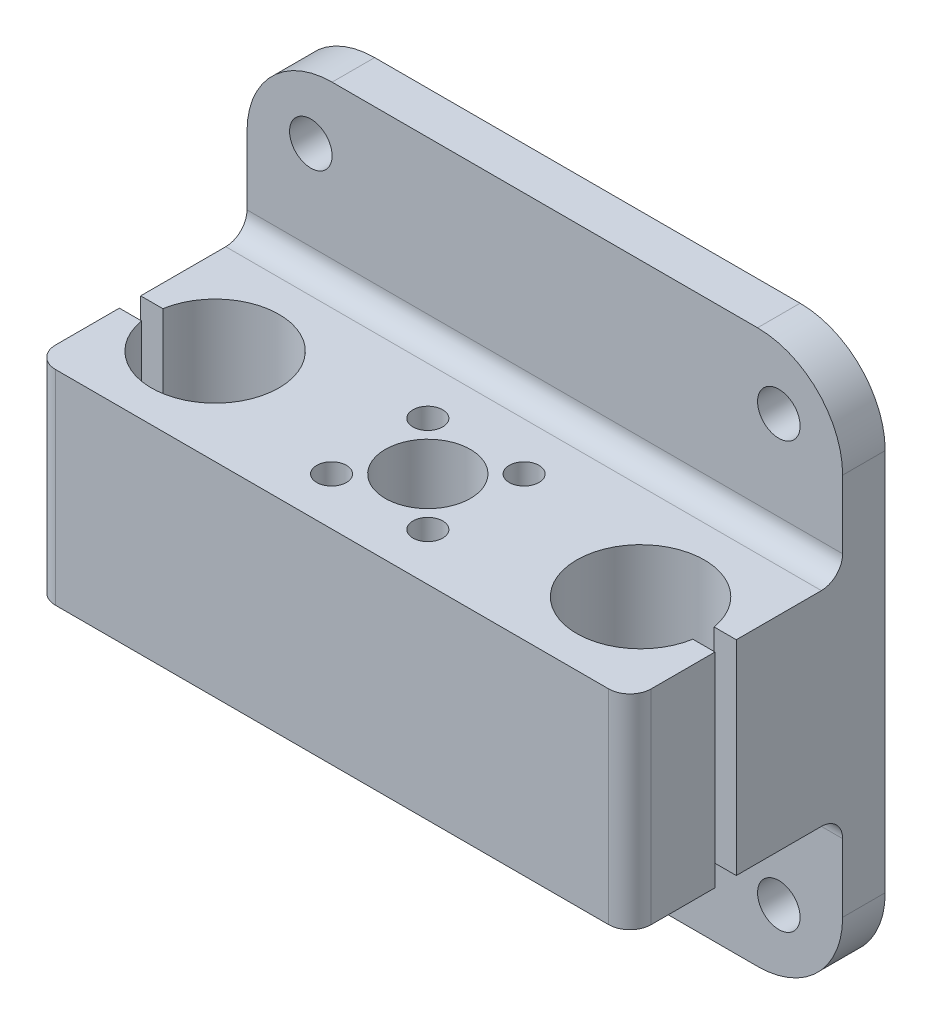
SolidWorks part; units mm, degrees
ref_plane "Front Plane" through (0, 0, 0) normal (0, 0, 1) x (1, 0, 0)
ref_plane "Top Plane" through (0, 0, 0) normal (0, 1, 0) x (1, 0, 0)
ref_plane "Right Plane" through (0, 0, 0) normal (1, 0, 0) x (0, 0, -1)
sketch "Sketch1" plane through (0, 0, 0) normal (0, 0, 1) x (1, 0, 0)
  line L0 (-50.4878, 10.6707) -> (19.5122, 10.6707) construction
  line L1 (-50.4878, 18.1707) -> (19.5122, 18.1707)
  line L2 (-50.4878, 18.1707) -> (-50.4878, -46.8293)
  line L3 (-50.4878, -46.8293) -> (19.5122, -46.8293)
  line L4 (19.5122, 18.1707) -> (19.5122, -46.8293)
  line L5 (19.5122, -39.3293) -> (-50.4878, -39.3293) construction
  circle A0 centre (-42.9878, 10.6707) radius 2.5
  circle A1 centre (12.0122, 10.6707) radius 2.5
  circle A2 centre (-42.9878, -39.3293) radius 2.5
  circle A3 centre (12.0122, -39.3293) radius 2.5
  dimension "D5" = 7.5
  dimension "D6" = 7.5
  dimension "D7" = 7.5
  dimension "D1" = 70
  dimension "D2" = 65
  dimension "D3" = 7.5
  dimension "D4" = 7.5
  dimension "D8" = 7.5
extrude "Boss-Extrude1" add sketch "Sketch1" along normal blind 5
fillet "Fillet1" radius 10 4 edges at (19.5122, -46.8293, 2.5) (19.5122, 18.1707, 2.5) (-50.4878, -46.8293, 2.5) (-50.4878, 18.1707, 2.5)
sketch "Sketch2" plane through (0, 0, 5) normal (0, 0, 1) x (1, 0, 0)
  line L0 (-50.4878, -14.3293) -> (19.5122, -14.3293) construction
  line L1 (-50.4878, 8.1707) -> (-50.4878, -36.8293) construction
  line L2 (19.5122, -36.8293) -> (19.5122, 8.1707) construction
  line L3 (-15.4878, 18.1707) -> (-15.4878, -46.8293) construction
  line L4 (9.5122, 18.1707) -> (-40.4878, 18.1707) construction
  line L5 (-40.4878, -46.8293) -> (9.5122, -46.8293) construction
  line L7 (19.5122, -26.3293) -> (-50.4878, -26.3293)
  line L8 (19.5122, -26.3293) -> (19.5122, -2.3293)
  line L9 (19.5122, -2.3293) -> (-50.4878, -2.3293)
  line L10 (-50.4878, -26.3293) -> (-50.4878, -2.3293)
  line L11 (19.5122, -26.3293) -> (-50.4878, -2.3293) construction
  line L12 (19.5122, -2.3293) -> (-50.4878, -26.3293) construction
  point P12 (-15.4878, -14.3293)
  dimension "D1" = 70
  dimension "D2" = 24
extrude "Boss-Extrude2" add sketch "Sketch2" along normal blind 25
fillet "Fillet2" radius 2.5 2 edges at (-15.4878, -26.3293, 5) (-15.4878, -2.3293, 5)
sketch "Sketch3" plane through (0, -2.3293, 0) normal (0, 1, 0) x (1, 0, 0)
  line L0 (-50.4878, -18.75) -> (19.5122, -18.75) construction
  line L1 (-50.4878, -30) -> (-50.4878, -7.5) construction
  line L2 (19.5122, -30) -> (19.5122, -7.5) construction
  circle A0 centre (-15.4878, -18.75) radius 5
  circle A1 centre (-40.4878, -18.75) radius 7.5
  circle A2 centre (9.5122, -18.75) radius 7.5
  dimension "D1" = 25
  dimension "D3" = 10
  dimension "D4" = 15
  dimension "D5" = 15
  dimension "D2" = 25
extrude "Cut-Extrude1" cut sketch "Sketch3" against normal blind 30
sketch "Sketch4" plane through (0, -2.3293, 0) normal (0, 1, 0) x (1, 0, 0)
  line L0 (-15.4878, -18.75) -> (-26.7542, -7.4836) construction
  line L1 (-26.7542, -7.4836) -> (-2.6885, -31.5494) construction
  line L2 (-2.6885, -31.5494) -> (-15.4878, -18.75) construction
  line L3 (-15.4878, -18.75) -> (-3.9042, -7.1664) construction
  line L4 (-3.9042, -7.1664) -> (-29.7686, -33.0308) construction
  line L6 (-15.4878, -18.75) -> (-26.0601, -10.2476) construction
  line L7 (-38.5195, -27.2656) -> (6.5388, -27.2656) construction
  circle A0 centre (-21.1447, -13.0931) radius 1.75
  circle A1 centre (-9.831, -13.0931) radius 1.75
  circle A2 centre (-9.831, -24.4069) radius 1.75
  circle A3 centre (-21.1447, -24.4069) radius 1.75
  dimension "D1" = 8
  dimension "D2" = 8
  dimension "D3" = 8
  dimension "D4" = 8
  dimension "D5" = 135
extrude "Cut-Extrude2" cut sketch "Sketch4" against normal blind 30
fillet "Fillet3" radius 2.5 2 edges at (19.5122, -14.3293, 30) (-50.4878, -14.3293, 30)
sketch "Sketch6" plane through (0, -2.3293, 0) normal (0, 1, 0) x (1, 0, 0)
  line L1 (-43.7209, -20) -> (-52.2547, -20)
  line L2 (-43.7209, -20) -> (-43.7209, -17.5)
  line L3 (-43.7209, -17.5) -> (-52.2547, -17.5)
  line L4 (-52.2547, -20) -> (-52.2547, -17.5)
  line L5 (-43.7209, -20) -> (-52.2547, -17.5) construction
  line L6 (-43.7209, -17.5) -> (-52.2547, -20) construction
  line L7 (10.5678, -20) -> (23.4566, -20)
  line L8 (10.5678, -20) -> (10.5678, -17.5)
  line L9 (10.5678, -17.5) -> (23.4566, -17.5)
  line L10 (23.4566, -20) -> (23.4566, -17.5)
  line L11 (10.5678, -20) -> (23.4566, -17.5) construction
  line L12 (10.5678, -17.5) -> (23.4566, -20) construction
  circle A0 centre (-40.4878, -18.75) radius 7.5 construction
  circle A1 centre (9.5122, -18.75) radius 7.5 construction
  point P0 (-47.9878, -18.75)
  point P7 (17.0122, -18.75)
  dimension "D1" = 2.5
  dimension "D2" = 2.5
extrude "Cut-Extrude3" cut sketch "Sketch6" against normal blind 30
